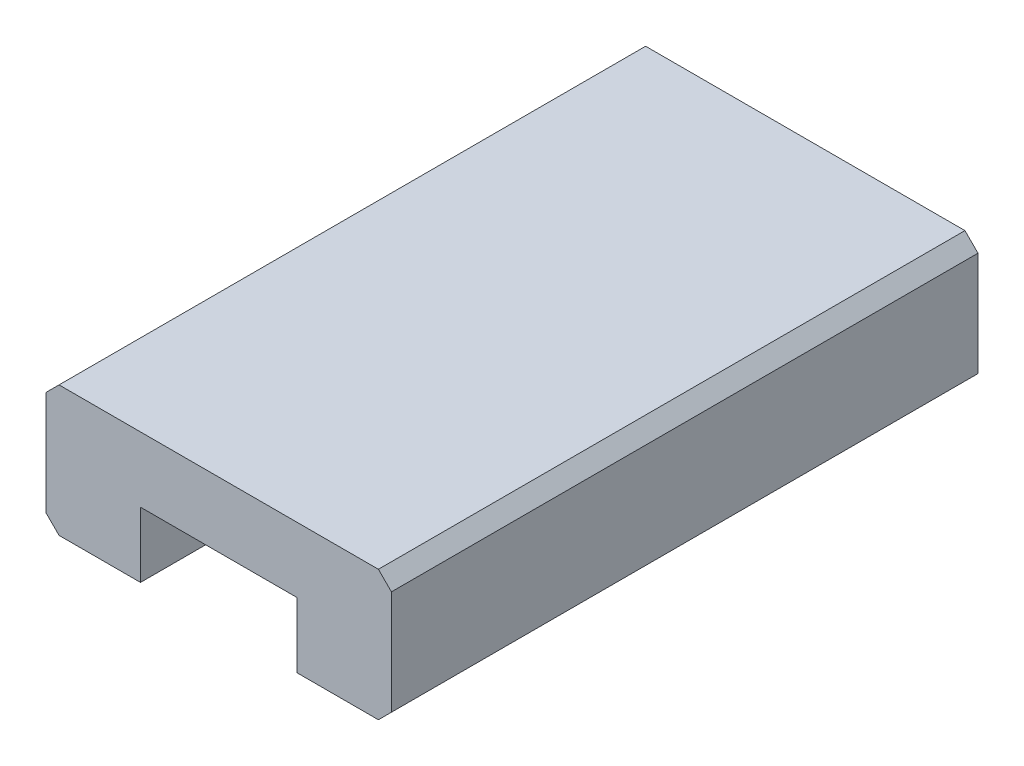
SolidWorks part; units mm, degrees
ref_plane "Front Plane" through (0, 0, 0) normal (0, 0, 1) x (1, 0, 0)
ref_plane "Top Plane" through (0, 0, 0) normal (0, 1, 0) x (1, 0, 0)
ref_plane "Right Plane" through (0, 0, 0) normal (1, 0, 0) x (0, 0, -1)
sketch "Sketch1" plane through (0, 0, 0) normal (0, 0, 1) x (1, 0, 0)
  line L13 (0, -55) -> (0, 55) construction
  line L14 (13.25, -5) -> (-13.25, -5)
  line L15 (-24.6481, 0) -> (21.2948, 0) construction
  line L16 (13.25, -5) -> (13.25, 5)
  line L17 (55, 0) -> (-55, 0) construction
  line L18 (13.25, 5) -> (-13.25, 5)
  line L19 (-13.25, -5) -> (-13.25, 5)
  line L20 (13.25, -5) -> (-13.25, 5) construction
  line L21 (13.25, 5) -> (-13.25, -5) construction
  line L22 (6, -5) -> (-6, -5)
  line L23 (6, -5) -> (6, 0)
  line L24 (6, 0) -> (-6, 0)
  line L25 (-6, -5) -> (-6, 0)
  line L26 (6, -5) -> (-6, 0) construction
  line L27 (6, 0) -> (-6, -5) construction
  point P0 (0, 0)
  point P7 (0, -2.5)
  dimension "D1" = 10
  dimension "D2" = 26.5
  dimension "D3" = 5
  dimension "D4" = 12
extrude "Boss-Extrude1" add sketch "Sketch1" against normal blind 45 contours L14 L25 L24 L23 L16 L18 L19
chamfer "Chamfer1" distance 1 angle 45 4 edges at (-13.25, 5, -22.5) (13.25, 5, -22.5) (-13.25, -5, -22.5) (13.25, -5, -22.5)
